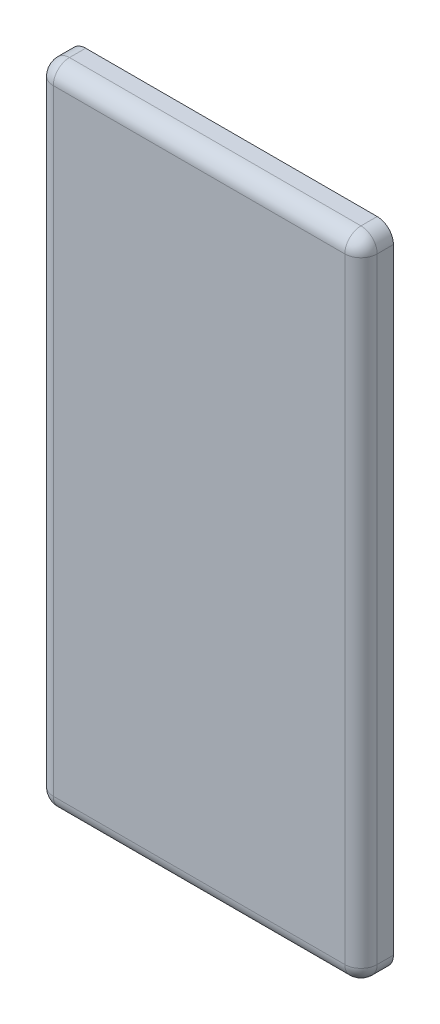
SolidWorks part; units mm, degrees
ref_plane "Top" through (0, 0, 0) normal (0, 0, 1) x (1, 0, 0)
ref_plane "Front" through (0, 0, 0) normal (0, 1, 0) x (1, 0, 0)
ref_plane "Right" through (0, 0, 0) normal (1, 0, 0) x (0, 0, -1)
sketch "Cap Sketch" plane through (0, 0, 0) normal (0, 0, 1) x (1, 0, 0)
  line L1 (-10, -20) -> (10, -20)
  line L2 (-10, -20) -> (-10, 20)
  line L3 (-10, 20) -> (10, 20)
  line L4 (10, -20) -> (10, 20)
  line L5 (-10, -20) -> (10, 20) construction
  line L6 (-10, 20) -> (10, -20) construction
  point P0 (0, 0)
  dimension "Width" = 20
  dimension "Length" = 40
extrude "Extrude Thickness" add sketch "Cap Sketch" along normal blind 2
fillet "Corner Fillets" radius 1 4 edges at (-10, -20, 1) (-10, 20, 1) (10, 20, 1) (10, -20, 1)
fillet "Top Edge Fillet" radius 1 8 edges at (-9.7071, 19.7071, 2) (0, 20, 2) (9.7071, 19.7071, 2) (10, 0, 2) (9.7071, -19.7071, 2) (0, -20, 2) (-9.7071, -19.7071, 2) (-10, 0, 2)
equation "\"M8 Close Fit Hole\"= 8.4"
